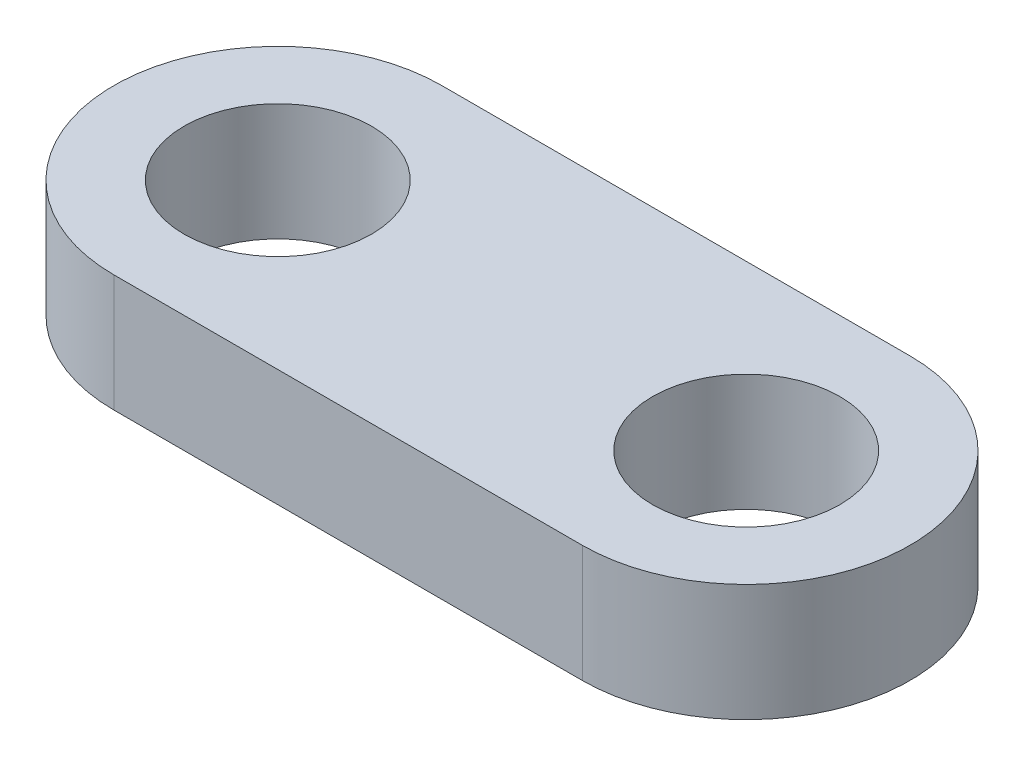
SolidWorks part; units mm, degrees
ref_plane "Front Plane" through (0, 0, 0) normal (0, 0, 1) x (1, 0, 0)
ref_plane "Top Plane" through (0, 0, 0) normal (0, 1, 0) x (1, 0, 0)
ref_plane "Right Plane" through (0, 0, 0) normal (1, 0, 0) x (0, 0, -1)
sketch "Sketch1" plane through (0, 0, 0) normal (0, 1, 0) x (1, 0, 0)
  line L0 (-10, 0) -> (10, 0) construction
  line L1 (-10, 7) -> (10, 7)
  line L2 (-10, -7) -> (10, -7)
  arc A0 (-10, 7) -> (-10, -7) centre (-10, 0) ccw
  arc A1 (10, -7) -> (10, 7) centre (10, 0) ccw
  circle A2 centre (-10, 0) radius 4
  circle A3 centre (10, 0) radius 4
  point P3 (0, 0)
  dimension "D1" = 7
  dimension "D3" = 8
  dimension "D4" = 8
  dimension "D2" = 20
extrude "Boss-Extrude1" add sketch "Sketch1" along normal blind 5
